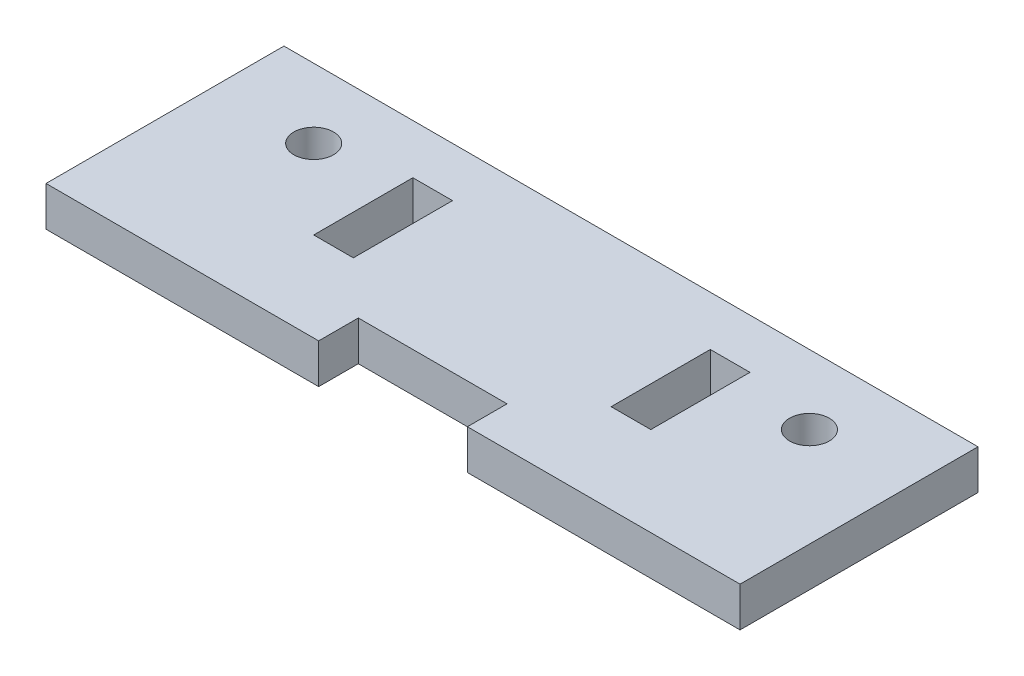
SolidWorks part; units mm, degrees
ref_plane "Front Plane" through (0, 0, 0) normal (0, 0, 1) x (1, 0, 0)
ref_plane "Top Plane" through (0, 0, 0) normal (0, 1, 0) x (1, 0, 0)
ref_plane "Right Plane" through (0, 0, 0) normal (1, 0, 0) x (0, 0, -1)
sketch "Sketch1" plane through (0, 0, 0) normal (0, 1, 0) x (1, 0, 0)
  line L0 (20, 24) -> (20, 0) construction
  line L1 (0, 0) -> (20, 0)
  line L2 (0, 0) -> (0, 24)
  line L3 (0, 24) -> (70, 24)
  line L4 (70, 0) -> (70, 24)
  line L5 (50, 24) -> (50, 0) construction
  line L6 (35, 24) -> (35, 4) construction
  line L7 (18, 19) -> (22, 19)
  line L8 (18, 19) -> (18, 9)
  line L9 (18, 9) -> (22, 9)
  line L10 (22, 19) -> (22, 9)
  line L11 (52, 9) -> (48, 9)
  line L12 (48, 19) -> (48, 9)
  line L13 (52, 19) -> (52, 9)
  line L14 (52, 19) -> (48, 19)
  line L15 (20, 0) -> (27.5, 0)
  line L17 (27.5, 0) -> (27.5, 24) construction
  line L26 (50, 0) -> (70, 0)
  line L27 (42.5, 0) -> (50, 0)
  line L30 (27.5, 0) -> (27.5, 4)
  line L31 (27.5, 4) -> (42.5, 4)
  line L32 (42.5, 0) -> (42.5, 4)
  circle A0 centre (10, 17) radius 2
  circle A2 centre (60, 17) radius 2
  dimension "D10" = 7.5
  dimension "D11" = 4
  dimension "D13" = 4
  dimension "D1" = 70
  dimension "D2" = 24
  dimension "D3" = 20
  dimension "D4" = 10
  dimension "D5" = 4
  dimension "D6" = 10
  dimension "D7" = 2
  dimension "D8" = 9
  dimension "D9" = 7
extrude "Boss-Extrude1" add sketch "Sketch1" along normal blind 4
